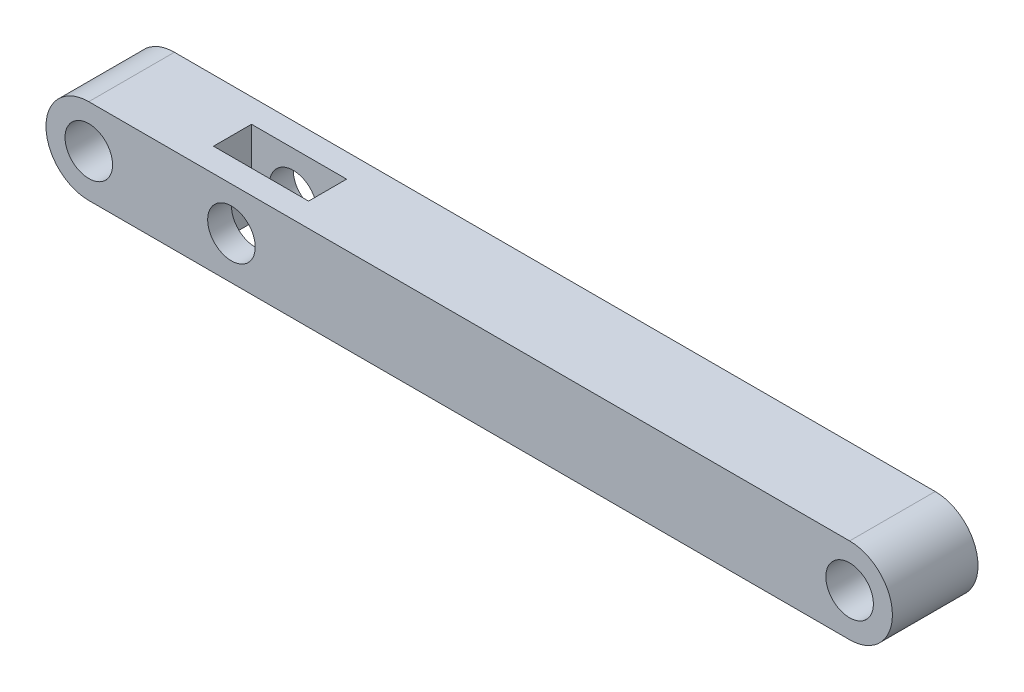
SolidWorks part; units mm, degrees
ref_plane "Front Plane" through (0, 0, 0) normal (0, 0, 1) x (1, 0, 0)
ref_plane "Top Plane" through (0, 0, 0) normal (0, 1, 0) x (1, 0, 0)
ref_plane "Right Plane" through (0, 0, 0) normal (1, 0, 0) x (0, 0, -1)
sketch "Sketch1" plane through (0, 0, 0) normal (0, 0, 1) x (1, 0, 0)
  line L0 (-30, 9) -> (130, 9)
  line L1 (130, -9) -> (-30, -9)
  circle A0 centre (0, 0) radius 5
  circle A1 centre (0, 0) radius 9 construction
  arc A2 (-30, 9) -> (-30, -9) centre (-30, 0) ccw
  circle A3 centre (130, 0) radius 5
  arc A4 (130, -9) -> (130, 9) centre (130, 0) ccw
  circle A5 centre (-30, 0) radius 5
  point P5 (-39, 0)
  point P8 (139, 0)
  dimension "D1" = 10
  dimension "D2" = 18
  dimension "D3" = 10
  dimension "D4" = 18
  dimension "D5" = 18
  dimension "D6" = 10
  dimension "D9" = 178
  dimension "D7" = 130
  dimension "D8" = 30
extrude "Boss-Extrude1" add sketch "Sketch1" along normal blind 18
sketch "Sketch3" plane through (0, 9, 0) normal (0, 1, 0) x (1, 0, 0)
  line L0 (130, -18) -> (-30, -18) construction
  line L1 (-8.7779, -5) -> (11.2221, -5)
  line L2 (-8.7779, -5) -> (-8.7779, -13)
  line L3 (-8.7779, -13) -> (11.2221, -13)
  line L4 (11.2221, -5) -> (11.2221, -13)
  dimension "D1" = 20
  dimension "D2" = 8
  dimension "D3" = 5
extrude "Cut-Extrude1" cut sketch "Sketch3" against normal blind 18
